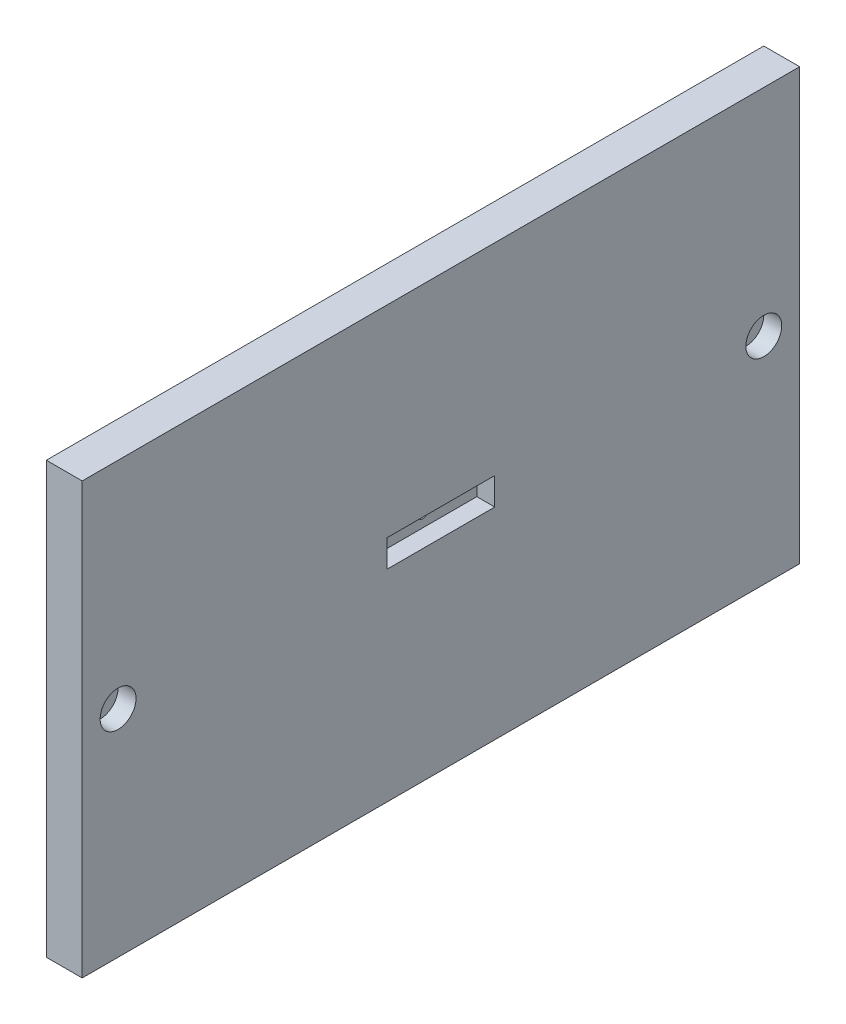
SolidWorks part; units mm, degrees
ref_plane "Front Plane" through (0, 0, 0) normal (0, 0, 1) x (1, 0, 0)
ref_plane "Top Plane" through (0, 0, 0) normal (0, 1, 0) x (1, 0, 0)
ref_plane "Right Plane" through (0, 0, 0) normal (1, 0, 0) x (0, 0, -1)
sketch "Sketch1" plane through (0, 0, 0) normal (1, 0, 0) x (0, 0, -1)
  line L1 (127, -76.2) -> (-127, -76.2)
  line L2 (127, -76.2) -> (127, 76.2)
  line L3 (127, 76.2) -> (-127, 76.2)
  line L4 (-127, -76.2) -> (-127, 76.2)
  line L5 (127, -76.2) -> (-127, 76.2) construction
  line L6 (127, 76.2) -> (-127, -76.2) construction
  point P0 (0, 0)
  dimension "D1" = 254
  dimension "D2" = 152.4
extrude "Boss-Extrude1" add sketch "Sketch1" along normal blind 12.7
sketch "Sketch2" plane through (12.7, 0, 0) normal (1, 0, 0) x (0, 0, -1)
  line L0 (0, 0) -> (101.6, 0) construction
  line L2 (0, 0) -> (131.9823, 76.2) construction
  line L3 (127, 76.2) -> (-127, 76.2) construction
  line L4 (-127, -76.2) -> (127, -76.2) construction
  circle A0 centre (65.1684, 37.625) radius 6.4897
  circle A1 centre (86.8201, 50.1256) radius 5.3581
  point P0 (0, 0)
  dimension "D3" = 12.9794
  dimension "D4" = 10.7163
  dimension "D1" = 30
  dimension "D2" = 75.25
  dimension "D5" = 25.0012
  dimension "D6" = 76.2
extrude "Cut-Extrude1" [suppressed] cut sketch "Sketch2" against normal through all
sketch "Sketch3" plane through (12.7, 0, 0) normal (1, 0, 0) x (0, 0, -1)
  line L0 (127, -76.2) -> (127, 76.2) construction
  line L1 (-127, 76.2) -> (-127, -76.2) construction
  circle A0 centre (114.3, 0) radius 6.35
  circle A1 centre (-114.3, 0) radius 6.35
  dimension "D1" = 12.7
  dimension "D2" = 12.7
  dimension "D3" = 12.7
  dimension "D4" = 12.7
extrude "Cut-Extrude2" cut sketch "Sketch3" against normal blind 6.35
hole_wizard "1/4 (0.25) Diameter Hole1" positions "Sketch4" profile "Sketch6" hole size "1/4" standard "ANSI Inch"
sketch "Sketch4" plane through (0, -76.2, 0) normal (0, -1, 0) x (-1, 0, 0)
  line L0 (-12.7, -127) -> (0, -127) construction
  line L1 (-12.7, 127) -> (0, 127) construction
  point P0 (-6.2363, -114.3)
  point P2 (-6.2363, 0)
  point P4 (-6.2363, 114.3)
  dimension "D1" = 12.7
  dimension "D2" = 12.7
  dimension "D3" = 127
sketch "Sketch6" plane through (6.2363, -76.2, 114.3) normal (1, 0, 0) x (0, 0, -1)
  line L0 (0, 0) -> (0, 14.6077)
  line L1 (0, 14.6077) -> (3.175, 12.7)
  line L2 (3.175, 12.7) -> (3.175, 0)
  line L5 (3.175, 0) -> (0, 0)
  line L10 (0, 14.6077) -> (-3.175, 12.7) construction
  line L11 (0, -6.35) -> (0, 107.95) construction
  dimension "Hole Dia." = 6.35
  dimension "Hole Depth" = 12.7
  dimension "Drill Angle" = 118
sketch "Sketch7" plane through (12.7, 0, 0) normal (1, 0, 0) x (0, 0, -1)
  line L1 (19.05, -4.826) -> (-19.05, -4.826)
  line L2 (19.05, -4.826) -> (19.05, 4.826)
  line L3 (19.05, 4.826) -> (-19.05, 4.826)
  line L4 (-19.05, -4.826) -> (-19.05, 4.826)
  line L5 (19.05, -4.826) -> (-19.05, 4.826) construction
  line L6 (19.05, 4.826) -> (-19.05, -4.826) construction
  point P0 (0, 0)
  dimension "D1" = 38.1
  dimension "D2" = 9.652
extrude "Cut-Extrude3" cut sketch "Sketch7" against normal blind 6.35
hole_wizard "#10-32 Tapped Hole1" positions "Sketch8" profile "Sketch10" tap size "#10-32" standard "ANSI Inch" end condition up to next
sketch "Sketch8" plane through (6.35, 0, 0) normal (1, 0, 0) x (0, 0, -1)
  line L0 (-19.05, 4.826) -> (-19.05, -4.826) construction
  point P0 (0, 0)
  dimension "D1" = 19.05
sketch "Sketch10" plane through (6.35, 0, 0) normal (0, 1, 0) x (0, 0, -1)
  line L0 (0, 0) -> (0, 6.35)
  line L1 (0, 6.35) -> (2.6543, 6.35)
  line L2 (2.0193, 5.715) -> (2.0193, 0)
  line L5 (2.0193, 0) -> (0, 0)
  line L7 (2.6543, 6.35) -> (2.0193, 5.715)
  line L8 (-2.6543, 6.35) -> (-2.0193, 5.715) construction
  line L11 (0, -6.35) -> (0, 107.95) construction
  dimension "Thru Tap Drill Dia." = 4.0386
  dimension "Thru Tap Drill Depth" = 6.35
  dimension "Far C'Sink Dia." = 5.3086
  dimension "Far C'Sink Angle" = 90
cosmetic thread "Hole Thread1" parameters "D2"=4.826
